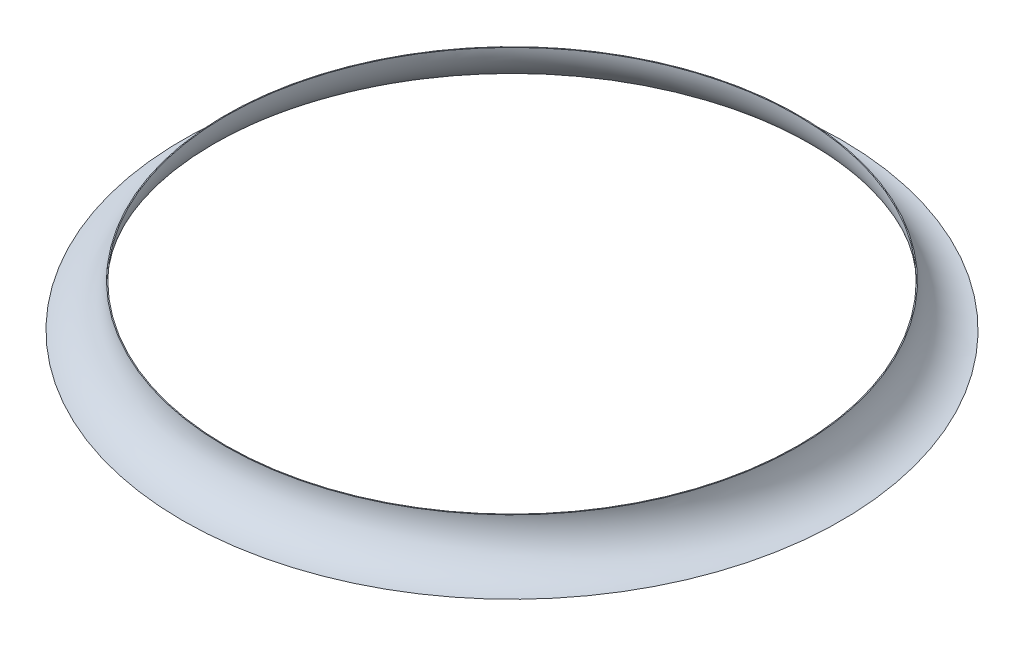
SolidWorks part; units mm, degrees
material "1023 Carbon Steel Sheet (SS)"
ref_plane "Front Plane" through (0, 0, 0) normal (0, 0, 1) x (1, 0, 0)
ref_plane "Top Plane" through (0, 0, 0) normal (0, 1, 0) x (1, 0, 0)
ref_plane "Right Plane" through (0, 0, 0) normal (1, 0, 0) x (0, 0, -1)
sketch "Sketch1" plane through (0, 0, 0) normal (1, 0, 0) x (0, 0, -1)
  line L0 (-1572.6253, 13.6514) -> (-1575.1253, 13.6514)
  line L1 (-1670.5031, -106.3486) -> (-1695.1253, -106.3486)
  line L2 (-772.1253, 13.6514) -> (-772.1253, -106.3486)
  arc A0 (-1695.1253, -106.3486) -> (-1575.1253, 13.6514) centre (-1695.1253, 13.6514) ccw
  arc A1 (-1670.5031, -106.3486) -> (-1572.6253, 13.6514) centre (-1695.1253, 13.6514) ccw
revolve "Revolve1" add sketch "Sketch1" angle 360 about L2
